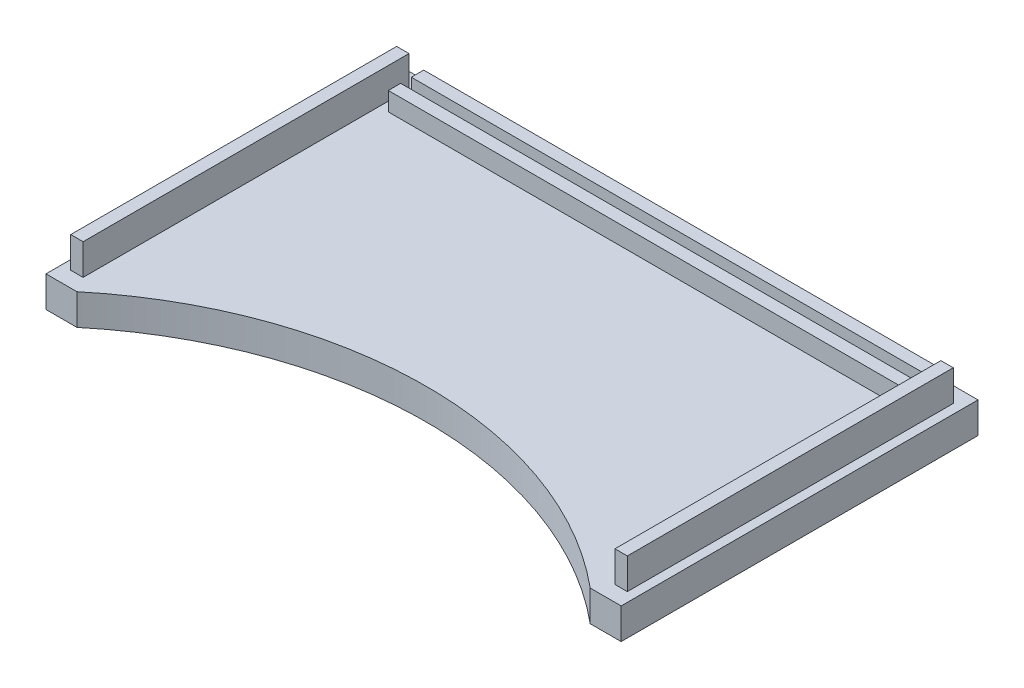
SolidWorks part; units mm, degrees
ref_plane "Front Plane" through (0, 0, 0) normal (0, 0, 1) x (1, 0, 0)
ref_plane "Top Plane" through (0, 0, 0) normal (0, 1, 0) x (1, 0, 0)
ref_plane "Right Plane" through (0, 0, 0) normal (1, 0, 0) x (0, 0, -1)
sketch "Sketch1" plane through (0, 0, 0) normal (0, 1, 0) x (1, 0, 0)
  line L1 (0, 0) -> (186, 0)
  line L2 (0, 0) -> (0, 115.4)
  line L3 (0, 115.4) -> (186, 115.4)
  line L4 (186, 0) -> (186, 115.4)
  dimension "D1" = 115.4
  dimension "D2" = 186
extrude "Boss-Extrude1" add sketch "Sketch1" along normal blind 10
sketch "Sketch4" plane through (0, 10, 0) normal (0, 1, 0) x (1, 0, 0)
  line L0 (186, 0) -> (186, 115.4) construction
  line L1 (186, 115.4) -> (0, 115.4) construction
  line L2 (10, 104.7) -> (176, 104.7)
  line L3 (10, 104.7) -> (10, 100.7)
  line L4 (10, 100.7) -> (176, 100.7)
  line L6 (10, 112.14) -> (176, 112.14)
  line L7 (176, 104.7) -> (176, 100.7)
  line L8 (0, 115.4) -> (0, 0) construction
  line L9 (10, 112.14) -> (10, 108.14)
  line L10 (10, 108.14) -> (176, 108.14)
  line L11 (176, 112.14) -> (176, 108.14)
  dimension "D1" = 4
  dimension "D2" = 10.7
  dimension "D3" = 10
  dimension "D4" = 10
  dimension "D5" = 3.44
  dimension "D6" = 4
  dimension "D7" = 10
  dimension "D8" = 10
sketch "Sketch5" plane through (0, 10, 0) normal (0, 1, 0) x (1, 0, 0)
  line L0 (10, 0) -> (10, 37.3827) construction
  line L1 (0, 0) -> (186, 0) construction
  line L2 (176, 0) -> (176, 15.4365) construction
  line L3 (0, 115.4) -> (0, 0) construction
  line L4 (186, 0) -> (186, 115.4) construction
  line L5 (93, 30) -> (0, 30) construction
  line L6 (176, 0) -> (10, 0)
  arc A0 (10, 0) -> (176, 0) centre (93, -99.8167) cw
  dimension "D1" = 10
  dimension "D2" = 10
  dimension "D3" = 30
extrude "Cut-Extrude5" cut sketch "Sketch5" against normal through all
extrude "Boss-Extrude3" add sketch "Sketch4" along normal blind 6
sketch "Sketch6" plane through (0, 10, 0) normal (0, 1, 0) x (1, 0, 0)
  line L0 (186, 115.4) -> (0, 115.4) construction
  line L1 (179, 110.4) -> (183, 110.4)
  line L2 (179, 110.4) -> (179, 5)
  line L3 (179, 5) -> (183, 5)
  line L4 (183, 110.4) -> (183, 5)
  line L5 (176, 0) -> (186, 0) construction
  line L6 (186, 0) -> (186, 115.4) construction
  dimension "D1" = 5
  dimension "D2" = 5
  dimension "D3" = 3
  dimension "D4" = 4
extrude "Boss-Extrude4" add sketch "Sketch6" along normal blind 10
sketch "Sketch7" plane through (0, 10, 0) normal (0, 1, 0) x (1, 0, 0)
  line L0 (186, 115.4) -> (0, 115.4) construction
  line L1 (3, 110.4) -> (7, 110.4)
  line L2 (3, 110.4) -> (3, 5)
  line L3 (3, 5) -> (7, 5)
  line L4 (7, 110.4) -> (7, 5)
  line L5 (0, 0) -> (10, 0) construction
  line L6 (0, 115.4) -> (0, 0) construction
  line L7 (10, 104.7) -> (10, 100.7) construction
  dimension "D1" = 5
  dimension "D2" = 5
  dimension "D3" = 3
  dimension "D4" = 3
extrude "Boss-Extrude5" add sketch "Sketch7" along normal blind 10
